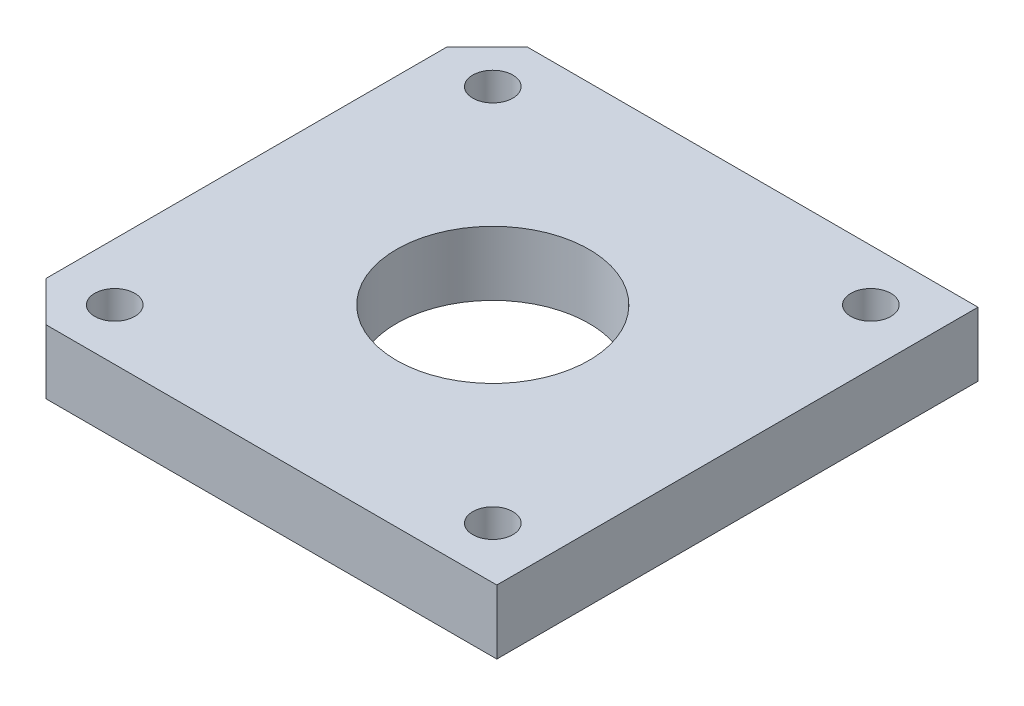
SolidWorks part; units mm, degrees
ref_plane "Front Plane" through (0, 0, 0) normal (0, 0, 1) x (1, 0, 0)
ref_plane "Top Plane" through (0, 0, 0) normal (0, 1, 0) x (1, 0, 0)
ref_plane "Right Plane" through (0, 0, 0) normal (1, 0, 0) x (0, 0, -1)
sketch "Sketch2" plane through (0, 0, 0) normal (0, 1, 0) x (1, 0, 0)
  line L1 (-18.7102, -30) -> (42.5, -30)
  line L2 (-18.7102, -30) -> (-18.7102, 30)
  line L3 (-18.7102, 30) -> (42.5, 30)
  line L4 (42.5, -30) -> (42.5, 30)
  point P0 (0, 0)
extrude "Extrude1" add sketch "Sketch2" along normal blind 8
chamfer "Chamfer1" distance 5 angle 45 2 edges at (-18.7102, 4, -30) (-18.7102, 4, 30)
sketch "Sketch3" plane through (0, 8, 0) normal (0, 1, 0) x (1, 0, 0)
  circle A0 centre (12, 0) radius 12
  circle A1 centre (-11.57, 23.57) radius 2.5
  circle A2 centre (35.57, 23.57) radius 2.5
  circle A3 centre (-11.57, -23.57) radius 2.5
  circle A4 centre (35.57, -23.57) radius 2.5
extrude "Cut-Extrude1" cut sketch "Sketch3" against normal through all
